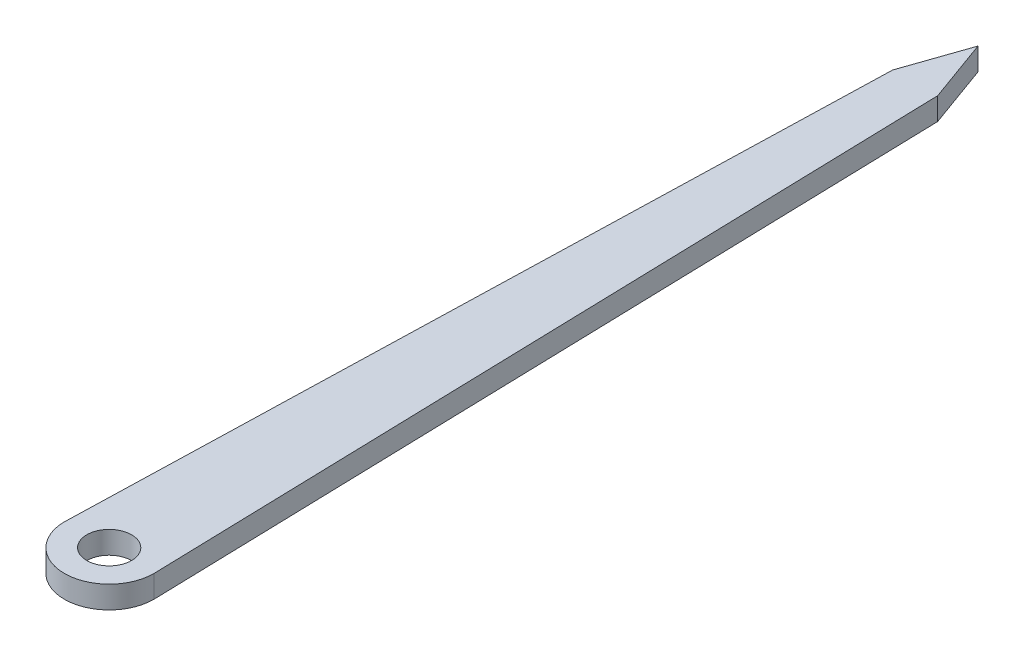
SolidWorks part; units mm, degrees
ref_plane "Přední rovina" through (0, 0, 0) normal (0, 0, 1) x (1, 0, 0)
ref_plane "Horní rovina" through (0, 0, 0) normal (0, 1, 0) x (1, 0, 0)
ref_plane "Pravá rovina" through (0, 0, 0) normal (1, 0, 0) x (0, 0, -1)
sketch "Skica1" plane through (0, 0, 0) normal (0, 1, 0) x (1, 0, 0)
  line L5 (25, 30) -> (195, 30)
  line L6 (0, 0) -> (220, 0)
  line L7 (0, 0) -> (0, 160)
  line L8 (0, 160) -> (220, 160)
  line L9 (220, 0) -> (220, 160)
  line L14 (106, 34) -> (108.0409, 105.9711)
  line L15 (108.0409, 105.9711) -> (110, 111.6422)
  line L16 (114, 34) -> (112.0409, 106)
  line L17 (112.0409, 106) -> (110, 111.6422)
  arc A1 (25, 30) -> (195, 30) centre (110, 30) cw
  circle A2 centre (110, 34) radius 2
  circle A3 centre (110, 34) radius 4
  point P6 (96.8851, 113.9821)
  point P8 (29.0741, 56)
  point P9 (41.2614, 80)
  point P10 (59, 98)
  point P11 (84.2318, 111)
  point P12 (135.7682, 111)
  point P13 (161, 98)
  point P14 (178.7386, 80)
  point P15 (190.9259, 56)
  point P16 (110, 115)
  point P17 (26, 43)
  point P19 (34.4752, 69)
  point P20 (49.69, 89.8974)
  point P21 (69.966, 104.9819)
  point P22 (122.9619, 114.0059)
  point P23 (147.8188, 106.1232)
  point P24 (170.7731, 89.4275)
  point P25 (185.5594, 68.933)
  point P26 (193.9442, 43.3553)
  dimension "D3" = 85
  dimension "D13" = 68
  dimension "D25" = 4
  dimension "D26" = 8
  dimension "D1" = 160
  dimension "D2" = 220
  dimension "D4" = 25
  dimension "D5" = 25
  dimension "D6" = 30
  dimension "D7" = 26
  dimension "D8" = 50
  dimension "D9" = 68
  dimension "D10" = 81
  dimension "D11" = 26
  dimension "D12" = 50
  dimension "D14" = 81
  dimension "D15" = 13
  dimension "D16" = 13
  dimension "D17" = 13
  dimension "D18" = 13
  dimension "D19" = 13
  dimension "D20" = 13
  dimension "D21" = 13
  dimension "D22" = 13
  dimension "D23" = 13
  dimension "D24" = 13
  dimension "D27" = 72
  dimension "D28" = 6
  dimension "D29" = 72
  dimension "D30" = 6
  dimension "D31" = 0
  dimension "D32" = 0
  dimension "D33" = 4
  dimension "D34" = 4
  dimension "D35" = 85
extrude "Přidat vysunutím3" add sketch "Skica1" along normal blind 2 contours A3 L16 L17 L15 L14 | A3 L16 L14 A2
sketch "Skica5" plane through (0, 2, 0) normal (0, 1, 0) x (1, 0, 0)
  circle A0 centre (110, 34) radius 4
  circle A1 centre (110, 34) radius 2
  dimension "D1" = 8
  dimension "D2" = 4
